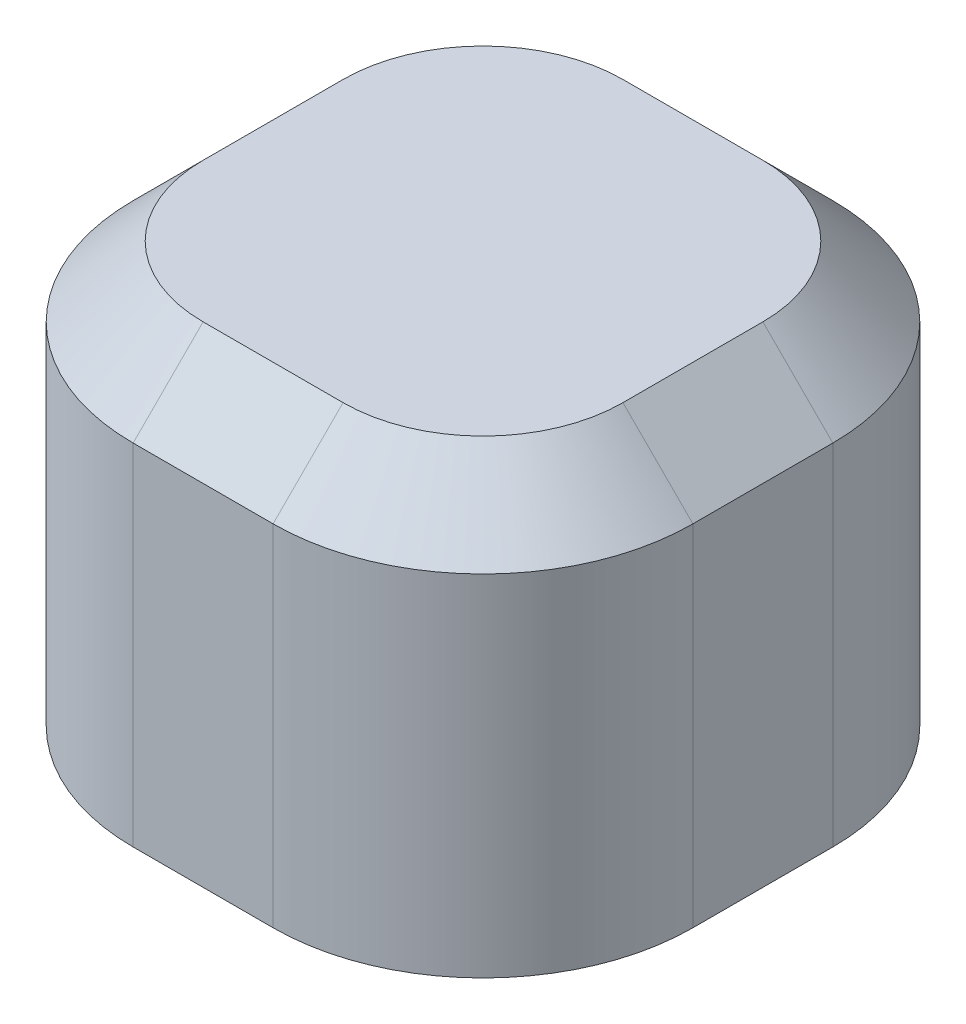
SolidWorks part; units mm, degrees
ref_plane "Alzado" through (0, 0, 0) normal (0, 0, 1) x (1, 0, 0)
ref_plane "Planta" through (0, 0, 0) normal (0, 1, 0) x (1, 0, 0)
ref_plane "Vista lateral" through (0, 0, 0) normal (1, 0, 0) x (0, 0, -1)
sketch "Croquis1" plane through (0, 0, 0) normal (0, 1, 0) x (1, 0, 0)
  line L1 (0, 0) -> (4, 0)
  line L2 (0, 0) -> (0, 4)
  line L3 (0, 4) -> (4, 4)
  line L4 (4, 0) -> (4, 4)
  dimension "D1" = 4
  dimension "D2" = 4
extrude "Saliente-Extruir1" add sketch "Croquis1" along normal blind 3
sketch "Croquis2" plane through (0, 0, 0) normal (0, -1, 0) x (1, 0, 0)
  line L0 (2, 0) -> (2, -4) construction
  line L1 (0.5, -0.5) -> (3.5, -0.5)
  line L2 (0.5, -0.5) -> (0.5, -3.5)
  line L3 (0.5, -3.5) -> (3.5, -3.5)
  line L4 (3.5, -0.5) -> (3.5, -3.5)
  line L5 (0.5, -0.5) -> (3.5, -3.5) construction
  line L6 (0.5, -3.5) -> (3.5, -0.5) construction
  line L7 (0, 0) -> (4, 0) construction
  line L8 (4, -4) -> (0, -4) construction
  line L9 (0, -2) -> (4, -2) construction
  line L10 (0, -4) -> (0, 0) construction
  line L11 (4, 0) -> (4, -4) construction
  point P0 (2, -2)
  point P17 (2, -2)
  dimension "D1" = 3
  dimension "D2" = 3
extrude "Cortar-Extruir1" cut sketch "Croquis2" against normal blind 1.5
fillet "Redondeo1" radius 1.5 4 edges at (0, 1.5, 0) (0, 1.5, -4) (4, 1.5, -4) (4, 1.5, 0)
chamfer "Chaflán1" distance 0.5 angle 45 8 edges at (0, 3, -2) (0.4393, 3, -0.4393) (0.4393, 3, -3.5607) (2, 3, 0) (2, 3, -4) (3.5607, 3, -0.4393) (3.5607, 3, -3.5607) (4, 3, -2)
